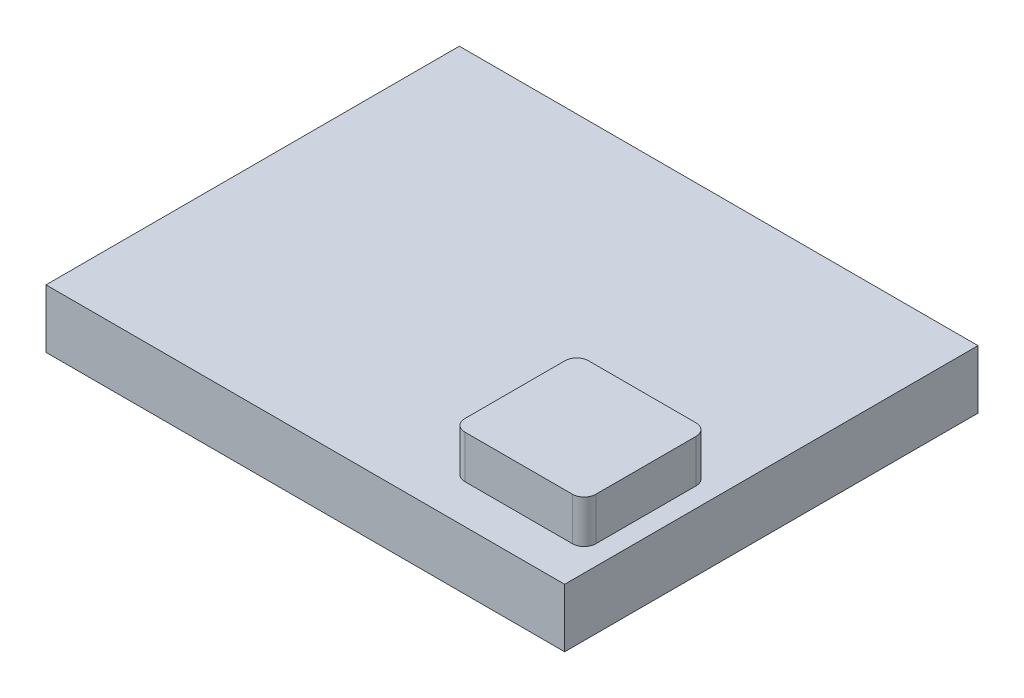
SolidWorks part; units mm, degrees
ref_plane "Front" through (0, 0, 0) normal (0, 0, 1) x (1, 0, 0)
ref_plane "Top" through (0, 0, 0) normal (0, 1, 0) x (1, 0, 0)
ref_plane "Right" through (0, 0, 0) normal (1, 0, 0) x (0, 0, -1)
sketch "Эскиз1" plane through (0, 0, 0) normal (0, 1, 0) x (1, 0, 0)
  line L1 (-6.65, -5.3) -> (6.65, -5.3)
  line L2 (-6.65, -5.3) -> (-6.65, 5.3)
  line L3 (-6.65, 5.3) -> (6.65, 5.3)
  line L4 (6.65, -5.3) -> (6.65, 5.3)
  line L5 (-6.65, -5.3) -> (6.65, 5.3) construction
  line L6 (-6.65, 5.3) -> (6.65, -5.3) construction
  point P0 (0, 0)
  dimension "D1" = 13.3
  dimension "D2" = 10.6
extrude "Бобышка-Вытянуть1" add sketch "Эскиз1" along normal blind 1.5
sketch "Эскиз2" plane through (0, 1.5, 0) normal (0, 1, 0) x (1, 0, 0)
  line L0 (-6.65, -5.3) -> (6.65, -5.3) construction
  line L1 (2.79, -1.13) -> (6.15, -1.13)
  line L2 (2.79, -1.13) -> (2.79, -4.3)
  line L3 (2.79, -4.3) -> (6.15, -4.3)
  line L4 (6.15, -1.13) -> (6.15, -4.3)
  line L5 (2.79, -1.13) -> (6.15, -4.3) construction
  line L6 (2.79, -4.3) -> (6.15, -1.13) construction
  line L7 (6.65, -5.3) -> (6.65, 5.3) construction
  point P0 (4.47, -2.715)
  dimension "D1" = 3.17
  dimension "D2" = 3.36
  dimension "D3" = 1
  dimension "D4" = 0.5
extrude "Бобышка-Вытянуть2" add sketch "Эскиз2" along normal blind 1.1 separate body
fillet "Скругление1" radius 0.3 4 edges at (2.79, 2.05, 1.13) (2.79, 2.05, 4.3) (6.15, 2.05, 1.13) (6.15, 2.05, 4.3)
